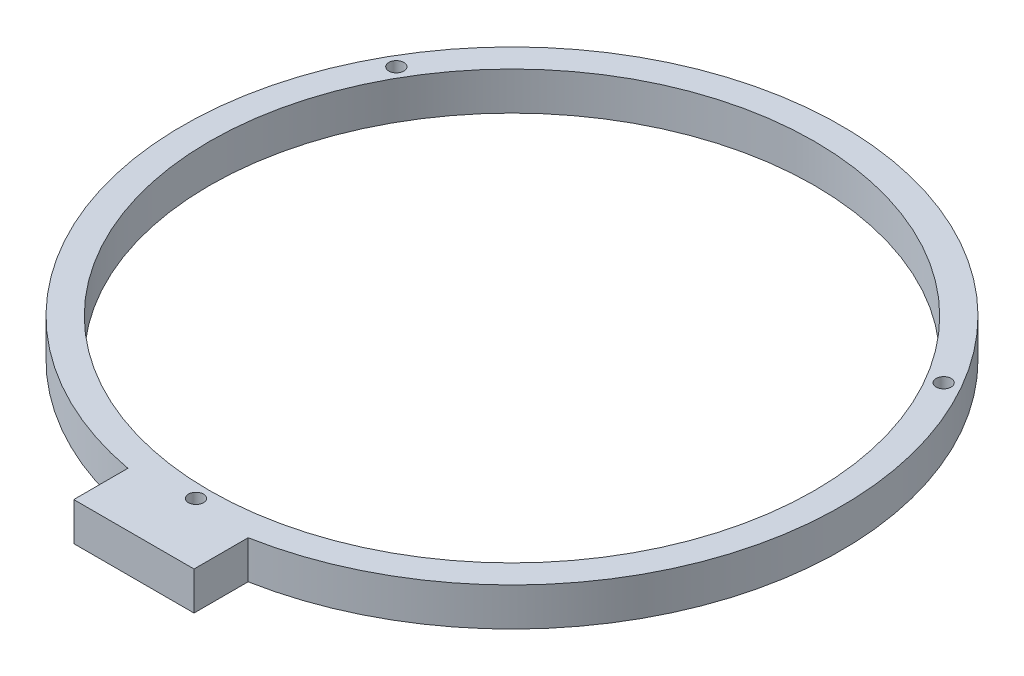
SolidWorks part; units mm, degrees
ref_plane "Front Plane" through (0, 0, 0) normal (0, 0, 1) x (1, 0, 0)
ref_plane "Top Plane" through (0, 0, 0) normal (0, 1, 0) x (1, 0, 0)
ref_plane "Right Plane" through (0, 0, 0) normal (1, 0, 0) x (0, 0, -1)
sketch "Sketch1" plane through (0, 0, 0) normal (0, 1, 0) x (1, 0, 0)
  line L0 (-10, -53.8799) -> (-10, -62.8799)
  line L1 (-10, -62.8799) -> (10, -62.8799)
  line L2 (10, -62.8799) -> (10, -53.8799)
  arc A0 (10, -53.8799) -> (-10, -53.8799) centre (0, 0) ccw
  circle A1 centre (0, 0) radius 50.3
  point P7 (0, 0)
  point P9 (0, -62.8799)
  dimension "D1" = 4.5
  dimension "D2" = 109.6
  dimension "D3" = 20
  dimension "D4" = 9
extrude "Boss-Extrude1" add sketch "Sketch1" along normal blind 6.35
sketch "Sketch2" plane through (0, 6.35, 0) normal (0, 1, 0) x (1, 0, 0)
  line L0 (0, -50.3) -> (0, -54.8) construction
  circle A0 centre (0, 0) radius 50.3 construction
  circle A1 centre (0, 0) radius 54.8 construction
  circle A2 centre (0, -52.55) radius 1.25
  point P9 (0, 0)
  dimension "D1" = 2.5
extrude "Cut-Extrude1" cut sketch "Sketch2" against normal up to next
pattern_circular "CirPattern1" count 3 over 360 about axis through (0, 0, 0) along (0, 1, 0) of "Cut-Extrude1"
